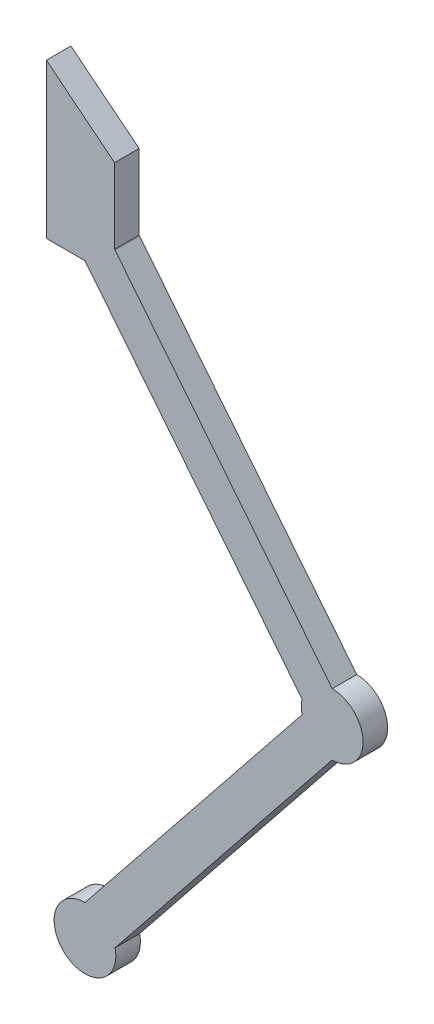
SolidWorks part; units mm, degrees
ref_plane "Front Plane" through (0, 0, 0) normal (0, 0, 1) x (1, 0, 0)
ref_plane "Top Plane" through (0, 0, 0) normal (0, 1, 0) x (1, 0, 0)
ref_plane "Right Plane" through (0, 0, 0) normal (1, 0, 0) x (0, 0, -1)
sketch "Sketch1" plane through (0, 0, 0) normal (0, 0, 1) x (1, 0, 0)
  line L0 (0, 0) -> (0, 4) construction
  line L1 (0, 4) -> (3.9031, 0.875) construction
  line L2 (0, 0) -> (1.9516, 2.4375) construction
  line L3 (1.9516, 2.4375) -> (32.0281, 40.0031) construction
  line L4 (0, 4) -> (28.125, 39.1281)
  line L5 (3.9031, 0.875) -> (32.0281, 36.0031)
  line L11 (28.125, 40.8781) -> (0, 76.0062)
  line L12 (32.0281, 44.0031) -> (3.9031, 79.1312)
  line L13 (28.125, 40.8781) -> (32.0281, 44.0031) construction
  line L14 (32.0281, 40.0031) -> (30.0766, 42.4406) construction
  line L15 (30.0766, 42.4406) -> (28.6848, 44.1789) construction
  line L19 (-5, 2.5) -> (-5, -87.5) construction
  line L20 (-12.5, 2.5) -> (2.5, 2.5) construction
  line L21 (-42.5, -87.5) -> (32.5, -87.5) construction
  line L22 (-5, 2.5) -> (-5, 94.7425) construction
  line L27 (3.9031, 79.1312) -> (3.8382, 79.2073)
  line L31 (-5, 96.0062) -> (-5, 76.0062)
  line L32 (0, 76.0062) -> (-5, 76.0062)
  line L33 (-5, 96.0062) -> (3.8382, 88.93)
  line L34 (3.8382, 88.93) -> (3.8382, 79.2073)
  arc A0 (0, 4) -> (3.9031, 0.875) centre (0, 0) ccw
  arc A1 (32.0281, 36.0031) -> (32.0281, 44.0031) centre (32.0281, 40.0031) ccw
  arc A2 (28.125, 39.1281) -> (28.125, 40.8781) centre (32.0281, 40.0031) cw
  dimension "D1" = 4
  dimension "D4" = 4
  dimension "D5" = 5
  dimension "D7" = 45
  dimension "D6" = 20
  dimension "D2" = 5
  dimension "D3" = 45
  dimension "D8" = 0.1
  dimension "D9" = 1.75
extrude "Boss-Extrude1" add sketch "Sketch1" along normal blind 3.18
